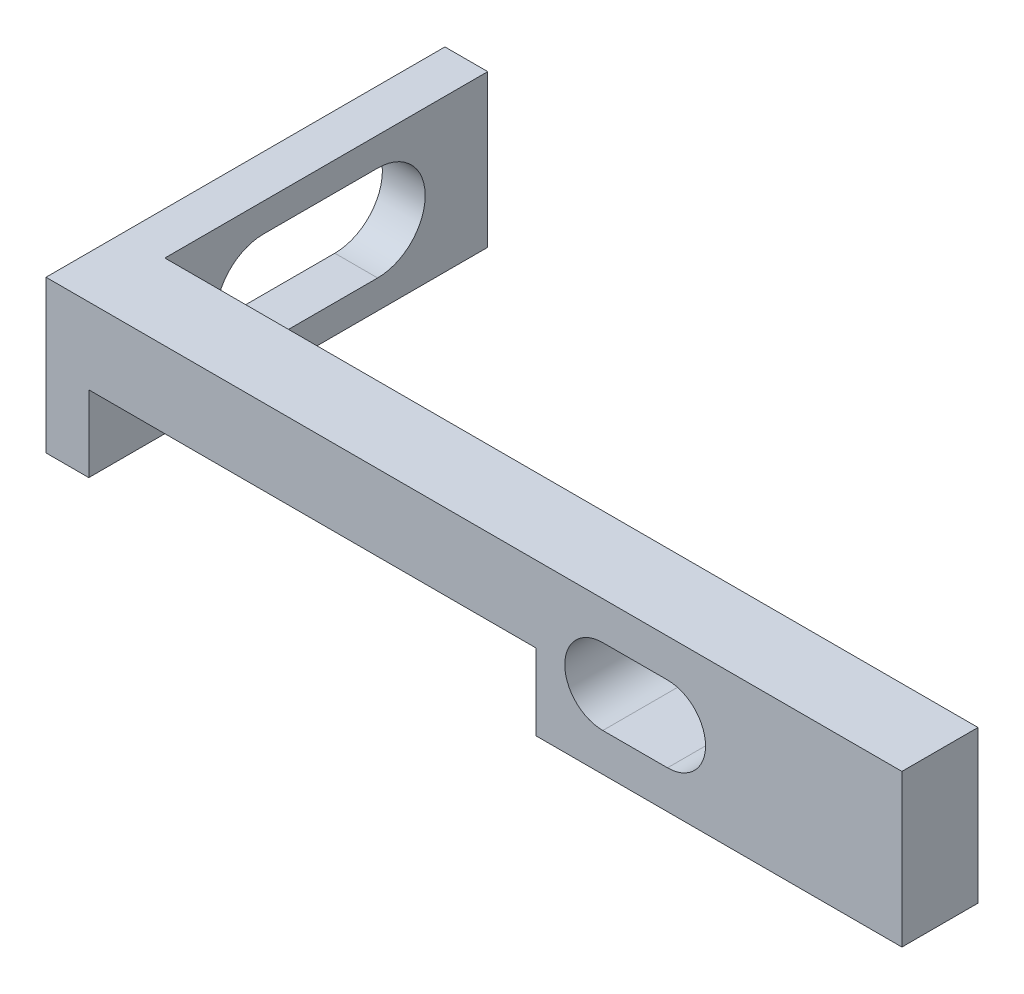
SolidWorks part; units mm, degrees
ref_plane "Front Plane" through (0, 0, 0) normal (0, 0, 1) x (1, 0, 0)
ref_plane "Top Plane" through (0, 0, 0) normal (0, 1, 0) x (1, 0, 0)
ref_plane "Right Plane" through (0, 0, 0) normal (1, 0, 0) x (0, 0, -1)
sketch "Sketch1" plane through (0, 0, 0) normal (0, 1, 0) x (1, 0, 0)
  line L1 (-22.5, 12.5) -> (22.5, 12.5)
  line L2 (-22.5, 12.5) -> (-22.5, -12.5)
  line L3 (-22.5, -12.5) -> (22.5, -12.5)
  line L4 (22.5, 12.5) -> (22.5, -12.5)
  line L5 (-22.5, 12.5) -> (22.5, -12.5) construction
  line L6 (-22.5, -12.5) -> (22.5, 12.5) construction
  point P0 (0, 0)
  dimension "D1" = 45
  dimension "D2" = 25
extrude "Boss-Extrude1" add sketch "Sketch1" along normal blind 4
sketch "Sketch5" plane through (0, 4, 0) normal (0, 1, 0) x (1, 0, 0)
  line L1 (-20.25, 8.5) -> (20.25, 8.5)
  line L2 (-20.25, 8.5) -> (-20.25, -8.5)
  line L3 (-20.25, -8.5) -> (20.25, -8.5)
  line L4 (20.25, 8.5) -> (20.25, -8.5)
  line L5 (-20.25, 8.5) -> (20.25, -8.5) construction
  line L6 (-20.25, -8.5) -> (20.25, 8.5) construction
  point P0 (0, 0)
  dimension "D1" = 17
  dimension "D2" = 40.5
extrude "Cut-Extrude2" cut sketch "Sketch5" against normal through all
sketch "Sketch6" plane through (0, 4, 0) normal (0, 1, 0) x (1, 0, 0)
  line L0 (22.5, -12.5) -> (22.5, 12.5) construction
  line L1 (-22.5, 12.5) -> (22.5, 12.5)
  line L2 (-22.5, 12.5) -> (-22.5, 8.4747)
  line L3 (-22.5, 8.4747) -> (22.5, 8.4747)
  line L4 (22.5, 12.5) -> (22.5, 8.4747)
extrude "Cut-Extrude3" cut sketch "Sketch6" against normal through all
sketch "Sketch13" plane through (0, 4, 0) normal (0, 1, 0) x (1, 0, 0)
  line L2 (20.25, 8.4747) -> (22.5, 8.4747)
  line L3 (20.25, 8.4747) -> (20.25, -12.5)
  line L4 (20.25, -12.5) -> (22.5, -12.5)
  line L5 (22.5, 8.4747) -> (22.5, -12.5)
extrude "Boss-Extrude3" add sketch "Sketch13" against normal blind 8
sketch "Sketch16" plane through (0, 4, 0) normal (0, 1, 0) x (1, 0, 0)
  line L1 (-22.5, -12.5) -> (-20.25, -12.5)
  line L2 (-22.5, -12.5) -> (-22.5, 8.4747)
  line L3 (-22.5, 8.4747) -> (-20.25, 8.4747)
  line L4 (-20.25, -12.5) -> (-20.25, 8.4747)
extrude "Boss-Extrude4" add sketch "Sketch16" against normal blind 8
sketch "Sketch19" plane through (0, 0, 0) normal (0, -1, 0) x (1, 0, 0)
  line L0 (-20.25, 8.5) -> (20.25, 8.5) construction
  line L1 (20.25, 12.5) -> (3.25, 12.5)
  line L2 (20.25, 12.5) -> (20.25, 8.5)
  line L3 (20.25, 8.5) -> (3.25, 8.5)
  line L4 (3.25, 12.5) -> (3.25, 8.5)
  dimension "D1" = 17
extrude "Boss-Extrude5" add sketch "Sketch19" along normal blind 4
sketch "Sketch21" plane through (0, 4, 0) normal (0, 1, 0) x (1, 0, 0)
  line L1 (20.25, -8.5) -> (22.5, -8.5)
  line L2 (20.25, -8.5) -> (20.25, 8.4747)
  line L3 (20.25, 8.4747) -> (22.5, 8.4747)
  line L4 (22.5, -8.5) -> (22.5, 8.4747)
extrude "Cut-Extrude7" cut sketch "Sketch21" against normal through all
sketch "Sketch25" plane through (-22.5, 0, 0) normal (-1, 0, 0) x (0, 0, 1)
  line L0 (3.3145, 0) -> (-2.6855, 0) construction
  line L1 (3.3145, -2.5) -> (-2.6855, -2.5)
  line L2 (3.3145, 2.5) -> (-2.6855, 2.5)
  arc A0 (3.3145, -2.5) -> (3.3145, 2.5) centre (3.3145, 0) ccw
  arc A1 (-2.6855, 2.5) -> (-2.6855, -2.5) centre (-2.6855, 0) ccw
  point P3 (0.3145, 0)
  dimension "D1" = 3
  dimension "D2" = 2.5
extrude "Cut-Extrude9" cut sketch "Sketch25" against normal through all
sketch "Sketch26" plane through (0, 0, 12.5) normal (0, 0, 1) x (1, 0, 0)
  line L1 (-20.25, 0) -> (5.75, 0)
  line L2 (-20.25, 0) -> (-20.25, -3.7687)
  line L3 (-20.25, -3.7687) -> (5.75, -3.7687)
  line L4 (5.75, 0) -> (5.75, -3.7687)
  point P5 (0, 0)
  dimension "D1" = 26
sketch "Sketch29" plane through (0, 0, 12.5) normal (0, 0, 1) x (1, 0, 0)
  line L0 (6.7748, 0) -> (10.1748, 0) construction
  line L1 (6.7748, 2) -> (10.1748, 2)
  line L2 (6.7748, -2) -> (10.1748, -2)
  arc A0 (6.7748, 2) -> (6.7748, -2) centre (6.7748, 0) ccw
  arc A1 (10.1748, -2) -> (10.1748, 2) centre (10.1748, 0) ccw
  point P4 (8.4748, 0)
  point P9 (0, 0)
  point P10 (9.6067, 0)
  point P11 (8.0379, 0)
  point P12 (0, 0)
  point P13 (10.4297, 0)
  point P14 (8.4748, 0)
  dimension "D1" = 1.7
  dimension "D2" = 2
extrude "Cut-Extrude14" cut sketch "Sketch29" against normal through all
